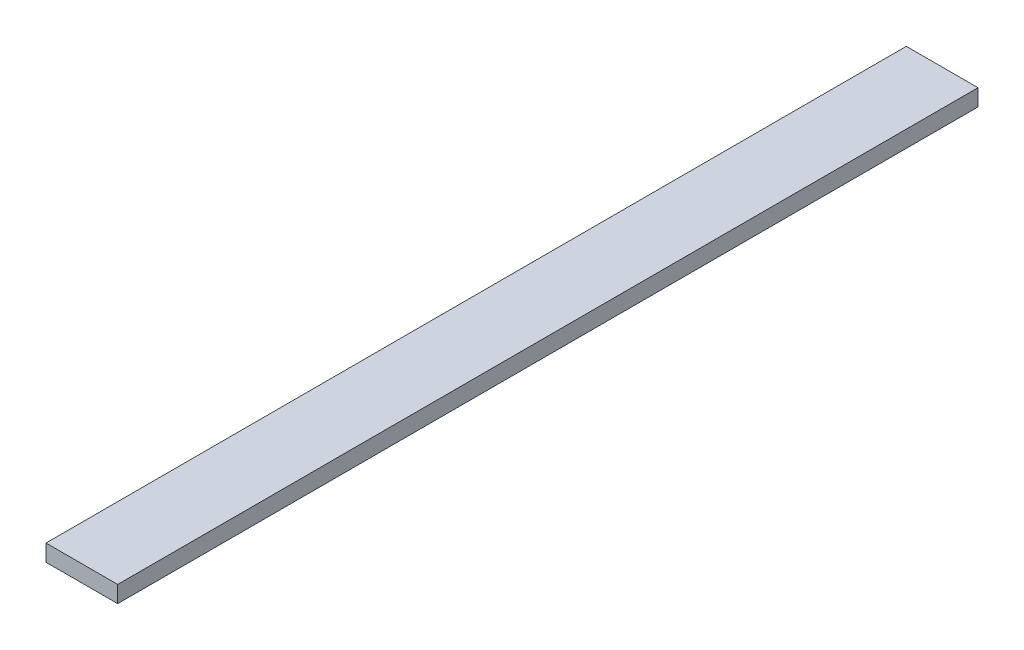
SolidWorks part; units mm, degrees
material "Mahogany"
ref_plane "Front Plane" through (0, 0, 0) normal (0, 0, 1) x (1, 0, 0)
ref_plane "Top Plane" through (0, 0, 0) normal (0, 1, 0) x (1, 0, 0)
ref_plane "Right Plane" through (0, 0, 0) normal (1, 0, 0) x (0, 0, -1)
sketch "Base_Sketch" plane through (0, 0, 0) normal (0, 1, 0) x (1, 0, 0)
  line L0 (-25.4, 0) -> (25.4, 0) construction
  line L1 (-25.4, 304.8) -> (25.4, 304.8)
  line L2 (-25.4, 304.8) -> (-25.4, -304.8)
  line L3 (-25.4, -304.8) -> (25.4, -304.8)
  line L4 (25.4, 304.8) -> (25.4, -304.8)
  line L5 (-25.4, 304.8) -> (25.4, -304.8) construction
  line L6 (-25.4, -304.8) -> (25.4, 304.8) construction
  line L7 (-13.59, -292.99) -> (13.59, -292.99) construction
  line L8 (13.59, 292.99) -> (13.59, -292.99) construction
  line L9 (-13.59, 292.99) -> (13.59, 292.99) construction
  line L10 (-13.59, 292.99) -> (-13.59, -292.99) construction
  line L11 (-37.21, -316.61) -> (37.21, -316.61) construction
  line L12 (37.21, 316.61) -> (37.21, -316.61) construction
  line L13 (-37.21, 316.61) -> (37.21, 316.61) construction
  line L14 (-37.21, 316.61) -> (-37.21, -316.61) construction
  line L16 (0, -304.8) -> (25.4, -304.8) construction
  point P0 (0, 0)
  dimension "D1" = 50.8
  dimension "D2" = 11.81
  dimension "D3" = 11.81
extrude "Boss-Extrude1" add sketch "Base_Sketch" along normal blind 11.81
equation "\"Material_Thickness\"= \"Material_Thickness@Petrov.Assembly\""
equation "\"D1@Boss-Extrude1\"=\"Material_Thickness\""
equation "\"Width\"= \"Accent_Width@Petrov.Assembly\""
equation "\"D1@Base_Sketch\"=\"Width\""
equation "\"D2@Base_Sketch\"=\"Material_Thickness\""
equation "\"D3@Base_Sketch\"=\"Material_Thickness\""
